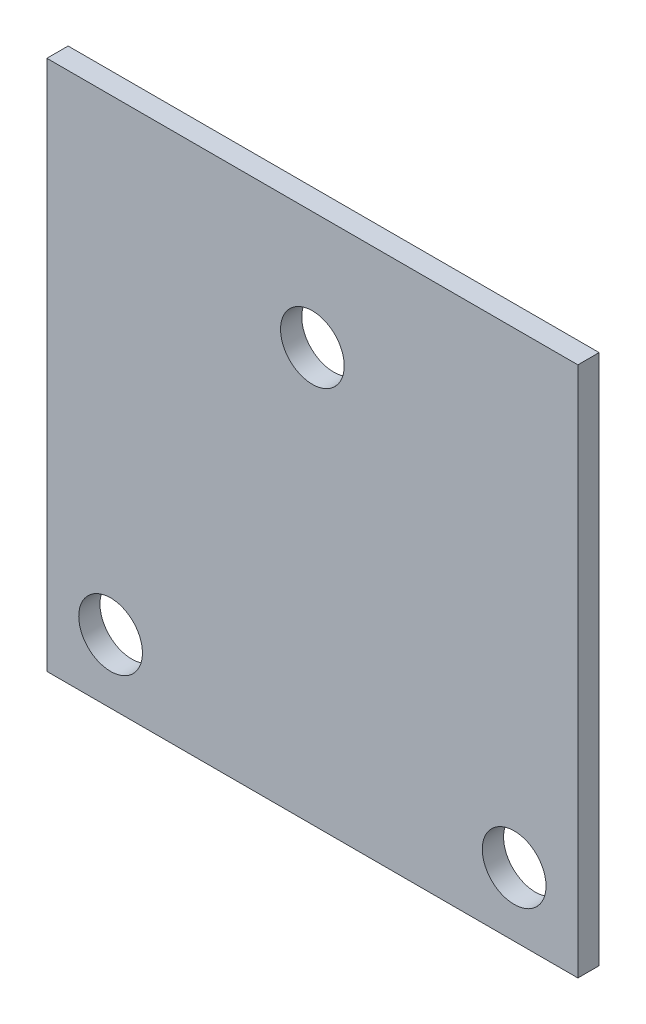
SolidWorks part; units mm, degrees
ref_plane "前视基准面" through (0, 0, 0) normal (0, 0, 1) x (1, 0, 0)
ref_plane "上视基准面" through (0, 0, 0) normal (0, 1, 0) x (1, 0, 0)
ref_plane "右视基准面" through (0, 0, 0) normal (1, 0, 0) x (0, 0, -1)
sketch "草图1" plane through (0, 0, 0) normal (0, 0, 1) x (1, 0, 0)
  line L0 (0, 0) -> (0, 6.9545) construction
  line L1 (12.5, -12.5) -> (-12.5, -12.5)
  line L2 (12.5, -12.5) -> (12.5, 12.5)
  line L3 (12.5, 12.5) -> (-12.5, 12.5)
  line L4 (-12.5, -12.5) -> (-12.5, 12.5)
  line L5 (12.5, -12.5) -> (-12.5, 12.5) construction
  line L6 (12.5, 12.5) -> (-12.5, -12.5) construction
  line L7 (0, 0) -> (0, -9.5) construction
  line L8 (0, -9.5) -> (9.5, -9.5) construction
  circle A0 centre (9.5, -9.5) radius 1.5
  circle A1 centre (-9.5, -9.5) radius 1.5
  circle A2 centre (0, 6.9545) radius 1.5
  point P0 (0, 0)
  dimension "D3" = 3
  dimension "D5" = 3
  dimension "D1" = 25
  dimension "D2" = 25
  dimension "D4" = 9.5
  dimension "D6" = 19
extrude "凸台-拉伸1" add sketch "草图1" along normal blind 1
